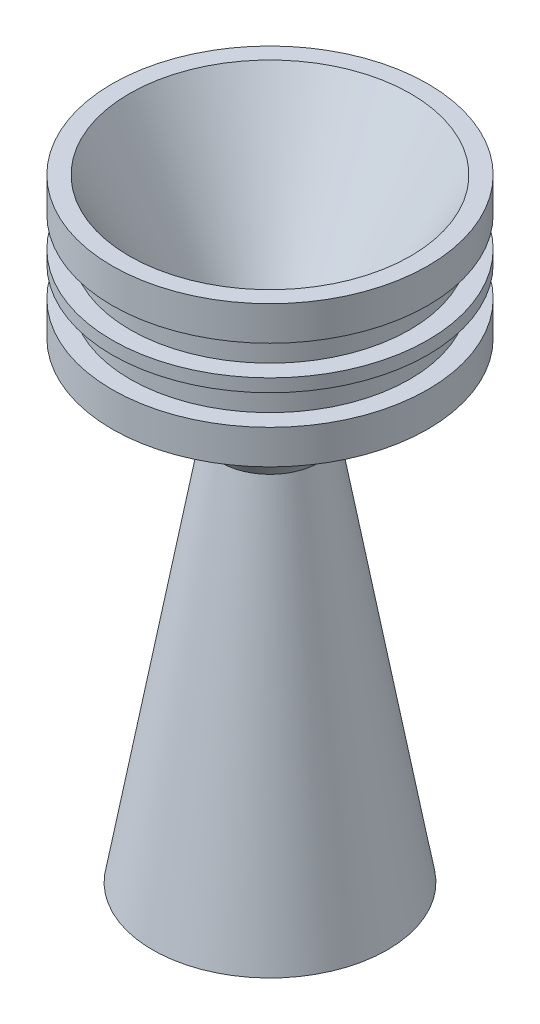
SolidWorks part; units mm, degrees
material "AISI 1020 Aço, laminado a frio"
ref_plane "Plano frontal" through (0, 0, 0) normal (0, 0, 1) x (1, 0, 0)
ref_plane "Plano superior" through (0, 0, 0) normal (0, 1, 0) x (1, 0, 0)
ref_plane "Plano direito" through (0, 0, 0) normal (1, 0, 0) x (0, 0, -1)
sketch "Esboço1" plane through (0, 0, 0) normal (0, 0, 1) x (1, 0, 0)
  line L0 (-10.3341, 0) -> (17.0613, 0) construction
  line L1 (0, 41.7492) -> (0, -48.2082) construction
  line L2 (0, 0) -> (-3.78, 0)
  line L3 (-3.78, 0) -> (-3.78, 2)
  line L4 (-3.78, 2) -> (-16.42, 23.8931)
  line L5 (-12.175, -47.6104) -> (-13.6981, -47.6104)
  line L6 (-3.78, 0) -> (-12.175, -47.6104)
  line L7 (-13.6981, -47.6104) -> (-5.7167, -2.3454)
  line L8 (-16.42, 23.8931) -> (-18.42, 23.8931)
  line L9 (-16.32, 19.8931) -> (-16.32, 16.3931)
  line L10 (-18.42, 23.8931) -> (-18.42, 19.8931)
  line L11 (-16.32, 13.1431) -> (-16.32, 62.4511) construction
  line L12 (-18.42, 19.8931) -> (-16.32, 19.8931)
  line L13 (-16.32, 16.3931) -> (-18.42, 16.3931)
  line L14 (-18.42, 16.3931) -> (-18.42, 14.8931)
  line L15 (-18.42, 14.8931) -> (-16.32, 14.8931)
  line L16 (-16.32, 14.8931) -> (-16.32, 11.3931)
  line L17 (-16.32, 11.3931) -> (-18.42, 11.3931)
  line L18 (-18.42, 11.3931) -> (-18.42, 7.3931)
  line L19 (-18.42, 7.3931) -> (-11.4706, 7.3931)
  line L21 (-11.4706, 7.3931) -> (-5.7167, -2.3454)
  dimension "D1" = 3.78
  dimension "D2" = 2
  dimension "D3" = 30
  dimension "D4" = 32.84
  dimension "D5" = 10
  dimension "D6" = 12.175
  dimension "D8" = 1.5
  dimension "D9" = 2
  dimension "D10" = 4
  dimension "D11" = 32.64
  dimension "D12" = 3.5
  dimension "D13" = 1.5
  dimension "D14" = 2.1
  dimension "D15" = 4
revolve "Revolução1" add sketch "Esboço1" angle 360 about L1
